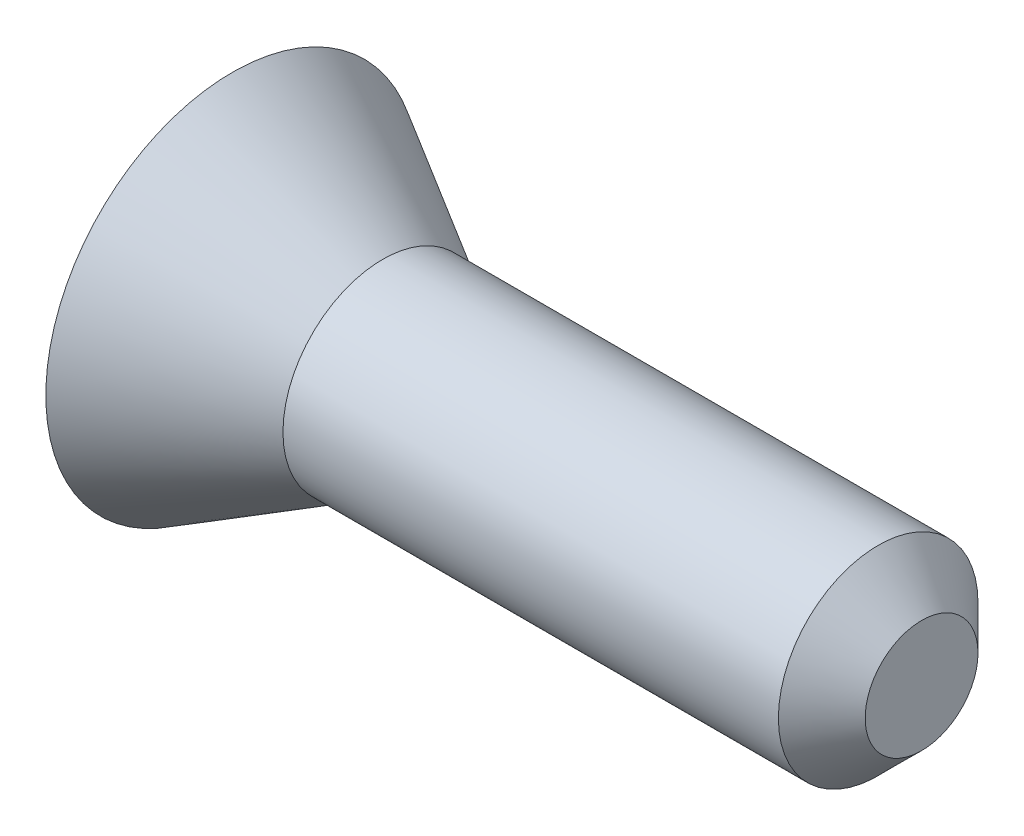
SolidWorks part; units mm, degrees
ref_plane "Front Plane" through (0, 0, 0) normal (0, 0, 1) x (1, 0, 0)
ref_plane "Top Plane" through (0, 0, 0) normal (0, 1, 0) x (1, 0, 0)
ref_plane "Right Plane" through (0, 0, 0) normal (1, 0, 0) x (0, 0, -1)
sketch "Sketch1" plane through (0, 0, 0) normal (0, 0, 1) x (1, 0, 0)
  line L0 (0, 2.7305) -> (0, 0)
  line L1 (0, 0) -> (10.0838, 0)
  line L2 (10.0838, 0) -> (10.0838, 0.8255)
  line L3 (10.0838, 0.8255) -> (9.4488, 1.4605)
  line L4 (9.4488, 1.4605) -> (2.1997, 1.4605)
  line L5 (2.1997, 1.4605) -> (0, 2.7305)
  line L6 (0, 0) -> (10.0838, 0) construction
revolve "Revolve1" add sketch "Sketch1" angle 360 about L6
ref_plane "Plane1" through (1.905, 0, 0) normal (1, 0, 0) x (0, 0, -1)
sketch "Sketch2" plane through (1.905, 0, 0) normal (1, 0, 0) x (0, 0, -1)
  line L0 (0.3429, 1.524) -> (-0.3429, 1.524)
  line L1 (-0.3429, 1.524) -> (-0.3429, 0.3429)
  line L2 (-0.3429, 0.3429) -> (-1.524, 0.3429)
  line L3 (-1.524, 0.3429) -> (-1.524, -0.3429)
  line L4 (-1.524, -0.3429) -> (-0.3429, -0.3429)
  line L5 (-0.3429, -0.3429) -> (-0.3429, -1.524)
  line L6 (-0.3429, -1.524) -> (0.3429, -1.524)
  line L7 (0.3429, -1.524) -> (0.3429, -0.3429)
  line L8 (0.3429, -0.3429) -> (1.524, -0.3429)
  line L9 (1.524, -0.3429) -> (1.524, 0.3429)
  line L10 (1.524, 0.3429) -> (0.3429, 0.3429)
  line L11 (0.3429, 0.3429) -> (0.3429, 1.524)
extrude "Cut-Extrude1" cut sketch "Sketch2" against normal up to next
